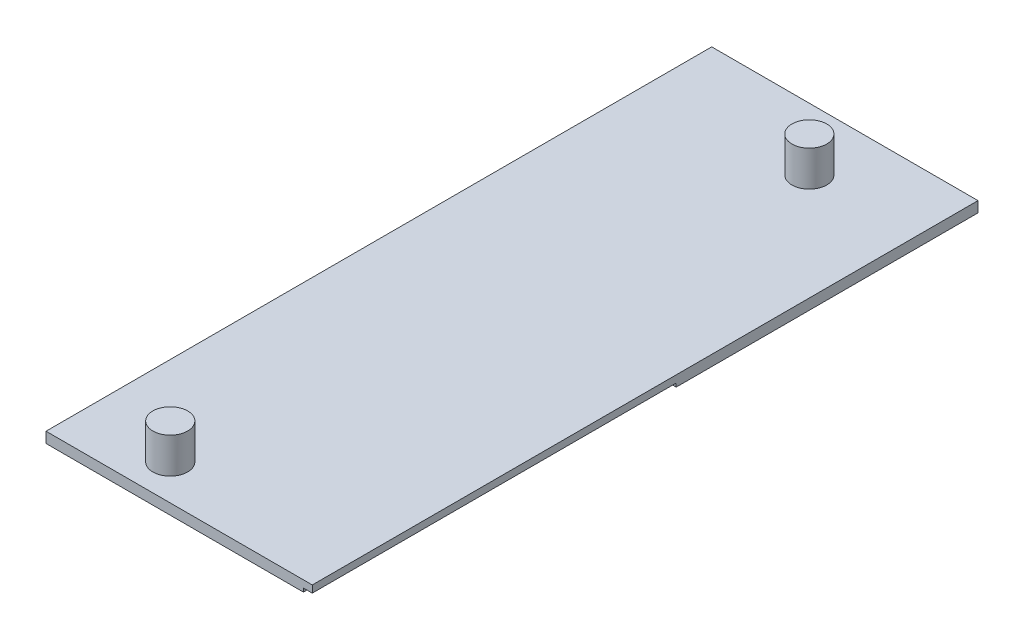
SolidWorks part; units mm, degrees
ref_plane "Front Plane" through (0, 0, 0) normal (0, 0, 1) x (1, 0, 0)
ref_plane "Top Plane" through (0, 0, 0) normal (0, 1, 0) x (1, 0, 0)
ref_plane "Right Plane" through (0, 0, 0) normal (1, 0, 0) x (0, 0, -1)
sketch "Sketch1" plane through (0, 0, 0) normal (0, 0, 1) x (1, 0, 0)
  line L1 (0, 0) -> (75, 0)
  line L2 (0, 0) -> (0, 3)
  line L3 (0, 3) -> (75, 3)
  line L4 (75, 0) -> (75, 3)
  dimension "D1" = 3
  dimension "D2" = 75
extrude "Boss-Extrude1" add sketch "Sketch1" along normal blind 187.5
sketch "Sketch2" plane through (0, 3, 0) normal (0, 1, 0) x (1, 0, 0)
  line L0 (0, -187.5) -> (0, 0) construction
  line L1 (187.5, 0) -> (-37.5, 0)
  line L2 (187.5, 0) -> (187.5, -187.5)
  line L3 (187.5, -187.5) -> (-37.5, -187.5)
  line L4 (-37.5, 0) -> (-37.5, -187.5)
  line L5 (175, -187.5) -> (-25, -187.5)
  line L6 (175, -187.5) -> (175, 0)
  line L7 (175, 0) -> (-25, 0)
  line L8 (-25, -187.5) -> (-25, 0)
  line L9 (75, -187.5) -> (0, -187.5) construction
  line L10 (75, 0) -> (0, 0) construction
  circle A0 centre (165, -177.5) radius 4.9
  circle A1 centre (125, -10) radius 4.9
  circle A2 centre (85, -177.5) radius 4.9
  circle A3 centre (45, -10) radius 4.9
  circle A4 centre (25, -177.5) radius 4.9
  circle A5 centre (-15, -10) radius 4.9
  circle A6 centre (45, -17.5) radius 4.9
  dimension "D4" = 10
  dimension "D5" = 10
  dimension "D6" = 9.8
  dimension "D7" = 9.8
  dimension "D8" = 10
  dimension "D9" = 40
  dimension "D11" = 10
  dimension "D12" = 10
  dimension "D13" = 80
  dimension "D14" = 80
  dimension "D15" = 10
  dimension "D16" = 10
  dimension "D17" = 60
  dimension "D18" = 60
  dimension "D19" = 9.8
  dimension "D20" = 9.8
  dimension "D21" = 9.8
  dimension "D22" = 9.8
  dimension "D23" = 9.8
  dimension "D24" = 7.5
  dimension "D25" = 70
  dimension "D1" = 225
  dimension "D2" = 12.5
  dimension "D3" = 12.5
  dimension "D10" = 25
extrude "Boss-Extrude2" add sketch "Sketch2" along normal blind 10 contours A4 | A6 | A3 A6 | A0 | A2 | A5
sketch "Sketch3" plane through (0, 0, 0) normal (0, -1, 0) x (1, 0, 0)
  line L0 (4, 43) -> (11, 43)
  line L1 (4, 43) -> (4, 10)
  line L2 (4, 10) -> (11, 10)
  line L3 (11, 43) -> (11, 10)
  line L4 (4, 47) -> (11, 47)
  line L5 (4, 47) -> (4, 80)
  line L6 (4, 80) -> (11, 80)
  line L7 (11, 47) -> (11, 80)
  line L9 (0, 187.5) -> (0, 0) construction
  line L10 (19, 43) -> (26, 43)
  line L11 (19, 43) -> (19, 10)
  line L12 (19, 10) -> (26, 10)
  line L13 (26, 43) -> (26, 10)
  line L14 (19, 47) -> (26, 47)
  line L15 (19, 47) -> (19, 80)
  line L16 (19, 80) -> (26, 80)
  line L17 (26, 47) -> (26, 80)
  line L18 (34, 43) -> (41, 43)
  line L19 (34, 43) -> (34, 10)
  line L20 (34, 10) -> (41, 10)
  line L21 (41, 43) -> (41, 10)
  line L22 (34, 47) -> (41, 47)
  line L23 (34, 47) -> (34, 80)
  line L24 (34, 80) -> (41, 80)
  line L25 (41, 47) -> (41, 80)
  line L26 (49, 43) -> (56, 43)
  line L27 (49, 43) -> (49, 10)
  line L28 (49, 10) -> (56, 10)
  line L29 (56, 43) -> (56, 10)
  line L30 (49, 47) -> (56, 47)
  line L31 (49, 47) -> (49, 80)
  line L32 (49, 80) -> (56, 80)
  line L33 (56, 47) -> (56, 80)
  line L34 (64, 43) -> (71, 43)
  line L35 (64, 43) -> (64, 10)
  line L36 (64, 10) -> (71, 10)
  line L37 (71, 43) -> (71, 10)
  line L38 (64, 47) -> (71, 47)
  line L39 (64, 47) -> (64, 80)
  line L40 (64, 80) -> (71, 80)
  line L41 (71, 47) -> (71, 80)
  line L42 (0, 0) -> (75, 0) construction
  line L56 (75, 187.5) -> (72.5, 187.5)
  line L57 (75, 187.5) -> (75, 85)
  line L58 (75, 85) -> (72.5, 85)
  line L59 (72.5, 187.5) -> (72.5, 85)
  dimension "D1" = 70
  dimension "D2" = 33
  dimension "D3" = 33
  dimension "D4" = 7
  dimension "D5" = 7
  dimension "D6" = 4
  dimension "D7" = 4
  dimension "D9" = 10
  dimension "D10" = 2.5
  dimension "D11" = 5
  dimension "D8" = 5
extrude "Cut-Extrude1" cut sketch "Sketch3" against normal blind 1
